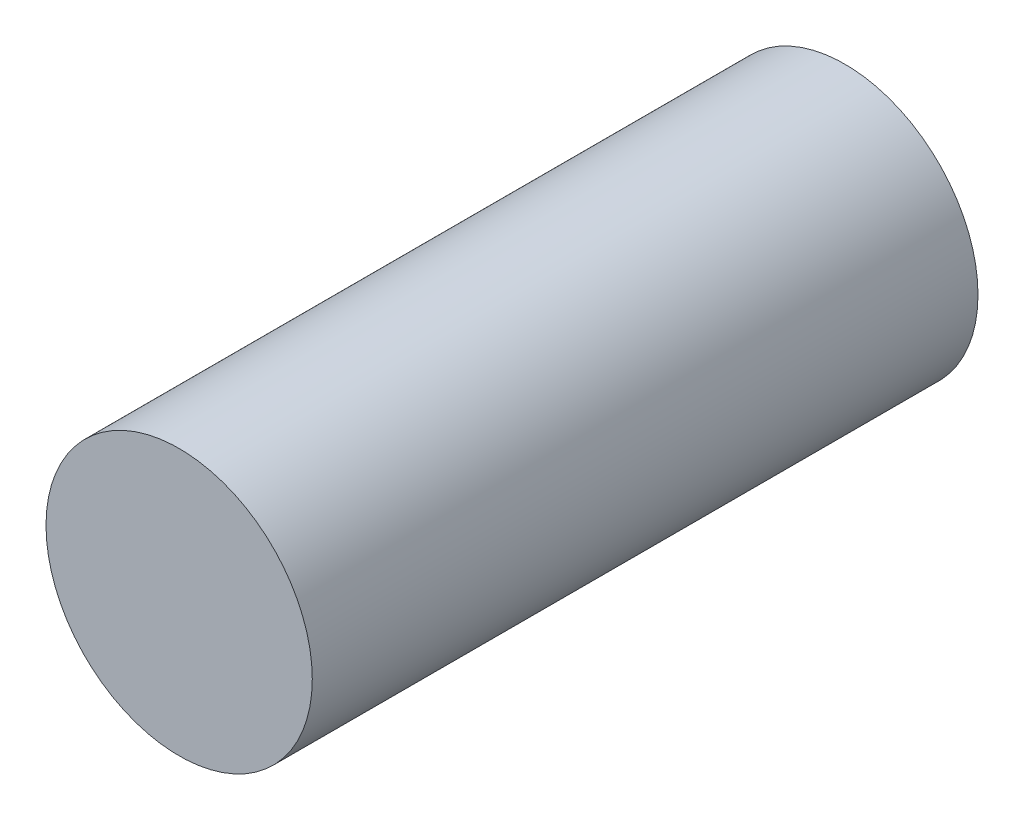
SolidWorks part; units mm, degrees
ref_plane "Спереди" through (0, 0, 0) normal (0, 0, 1) x (1, 0, 0)
ref_plane "Сверху" through (0, 0, 0) normal (0, 1, 0) x (1, 0, 0)
ref_plane "Справа" through (0, 0, 0) normal (1, 0, 0) x (0, 0, -1)
sketch "Эскиз1" plane through (0, 0, 0) normal (0, 0, 1) x (1, 0, 0)
  circle A0 centre (0, 0) radius 4
extrude "Planet_pin" add sketch "Эскиз1" along normal blind 20 from offset 27
